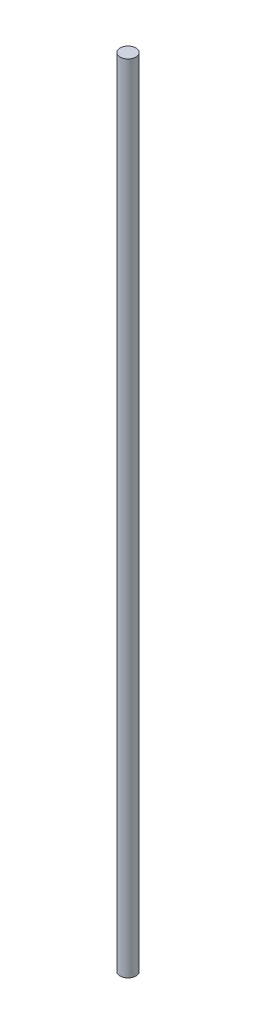
SolidWorks part; units mm, degrees
ref_plane "정면" through (0, 0, 0) normal (0, 0, 1) x (1, 0, 0)
ref_plane "윗면" through (0, 0, 0) normal (0, 1, 0) x (1, 0, 0)
ref_plane "우측면" through (0, 0, 0) normal (1, 0, 0) x (0, 0, -1)
sketch "스케치1" plane through (0, 0, 0) normal (0, 1, 0) x (1, 0, 0)
  circle A0 centre (0, 0) radius 4
  dimension "D1" = 8
extrude "보스-돌출1" add sketch "스케치1" along normal blind 400
